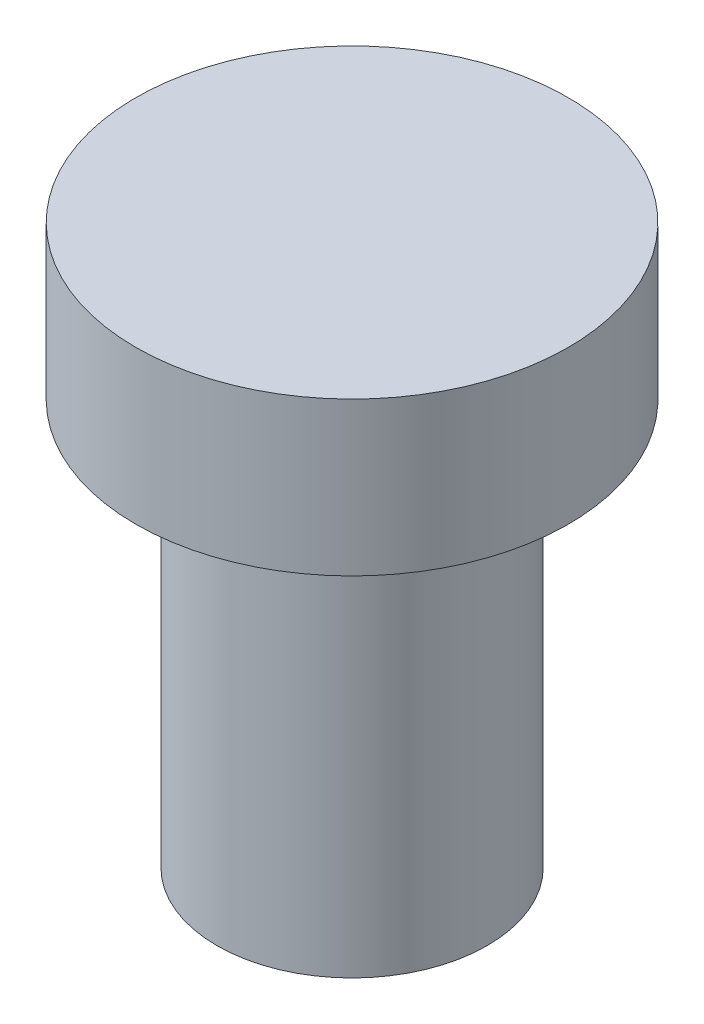
SolidWorks part; units mm, degrees
ref_plane "Plan de face" through (0, 0, 0) normal (0, 0, 1) x (1, 0, 0)
ref_plane "Plan de dessus" through (0, 0, 0) normal (0, 1, 0) x (1, 0, 0)
ref_plane "Plan de droite" through (0, 0, 0) normal (1, 0, 0) x (0, 0, -1)
sketch "Esquisse1" plane through (0, 0, 0) normal (0, 1, 0) x (1, 0, 0)
  circle A0 centre (0, 0) radius 2.4
  dimension "D1" = 4.8
extrude "Boss.-Extru.1" add sketch "Esquisse1" along normal blind 1.7
sketch "Esquisse2" plane through (0, 0, 0) normal (0, -1, 0) x (1, 0, 0)
  circle A0 centre (0, 0) radius 1.5
  dimension "D1" = 3
extrude "Boss.-Extru.2" add sketch "Esquisse2" along normal blind 4.5
